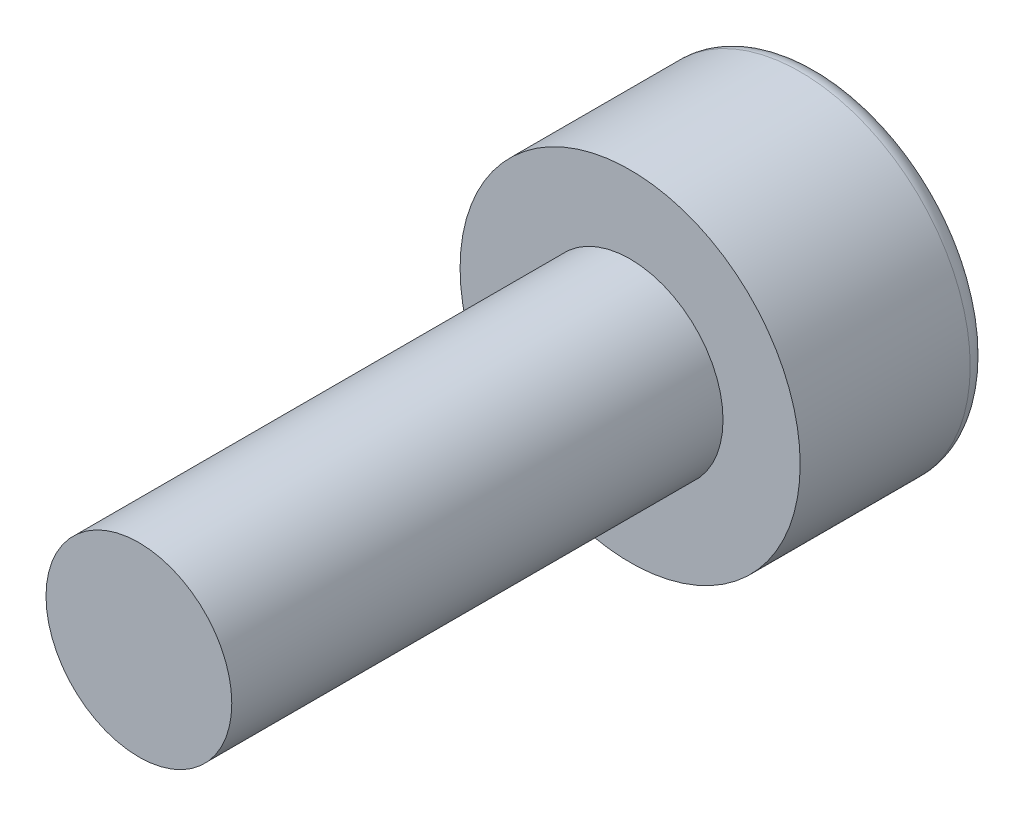
SolidWorks part; units mm, degrees
material "Acero aleado"
ref_plane "Alzado" through (0, 0, 0) normal (0, 0, 1) x (1, 0, 0)
ref_plane "Planta" through (0, 0, 0) normal (0, 1, 0) x (1, 0, 0)
ref_plane "Vista lateral" through (0, 0, 0) normal (1, 0, 0) x (0, 0, -1)
sketch "Croquis1" plane through (0, 0, 0) normal (0, 0, 1) x (1, 0, 0)
  circle A0 centre (0, 0) radius 1.475
  dimension "D1" = 2.95
extrude "Saliente-Extruir1" add sketch "Croquis1" along normal blind 7.8
sketch "Croquis2" plane through (0, 0, 0) normal (0, 0, -1) x (-1, 0, 0)
  circle A0 centre (0, 0) radius 2.7
  dimension "D1" = 5.4
extrude "Saliente-Extruir2" add sketch "Croquis2" along normal blind 3
sketch "Croquis3" plane through (0, 0, -3) normal (0, 0, -1) x (-1, 0, 0)
  line L1 (0, -1.7767) -> (1.5387, -0.8884)
  line L2 (1.5387, -0.8884) -> (1.5387, 0.8884)
  line L3 (1.5387, 0.8884) -> (0, 1.7767)
  line L4 (0, 1.7767) -> (-1.5387, 0.8884)
  line L5 (-1.5387, 0.8884) -> (-1.5387, -0.8884)
  line L6 (-1.5387, -0.8884) -> (0, -1.7767)
  circle A0 centre (0, 0) radius 1.5387 construction
extrude "Cortar-Extruir1" cut sketch "Croquis3" against normal blind 2.5
fillet "Redondeo1" radius 0.3 1 edges at (-2.7, 0, -3)
